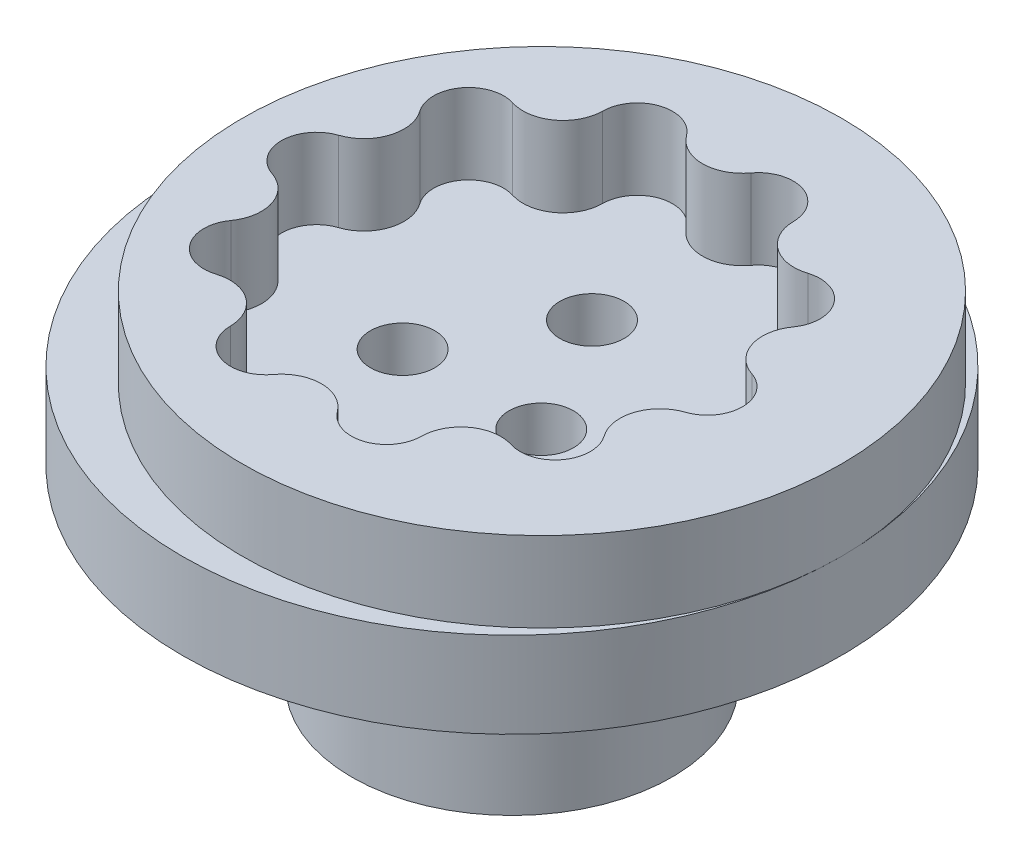
SolidWorks part; units mm, degrees
material "6061 Alloy"
ref_plane "Front" through (0, 0, 0) normal (0, 0, 1) x (1, 0, 0)
ref_plane "Top" through (0, 0, 0) normal (0, 1, 0) x (1, 0, 0)
ref_plane "Right" through (0, 0, 0) normal (1, 0, 0) x (0, 0, -1)
sketch "Sketch1" plane through (0, 0, 0) normal (0, 1, 0) x (1, 0, 0)
  circle A0 centre (0, 0) radius 26.1937 construction
  circle A1 centre (0, 0) radius 26.143
  dimension "D1" = 52.3875
  dimension "D2" = 0.0508
extrude "Boss-Extrude1" add sketch "Sketch1" against normal blind 6.8104
sketch "Sketch2" plane through (0, -6.8104, 0) normal (0, -1, 0) x (1, 0, 0)
  circle A0 centre (0, 0) radius 12.7
  dimension "D1" = 25.4
extrude "Boss-Extrude2" add sketch "Sketch2" along normal blind 15.0812
sketch "Sketch3" plane through (0, 0, 0) normal (0, 1, 0) x (1, 0, 0)
  line L0 (0, 0) -> (0, 26.143) construction
  line L1 (0, 0) -> (15.3664, 21.1501) construction
  arc A0 (2.553, 16.4005) -> (7.5745, 14.7689) centre (4.7912, 14.7457) cw
  circle A2 centre (0, 0) radius 18.288 construction
  arc A3 (0, 15.113) -> (2.553, 16.4005) centre (0, 18.288) ccw
  arc A4 (8.8832, 12.2267) -> (7.5745, 14.7689) centre (10.7494, 14.7953) cw
  arc A5 (8.8832, 12.2267) -> (11.7054, 11.7676) centre (10.7494, 14.7953) ccw
  arc A6 (11.7054, 11.7676) -> (14.8088, 7.4961) centre (12.5434, 9.1133) cw
  arc A7 (14.3733, 4.6702) -> (14.8088, 7.4961) centre (17.3929, 5.6513) cw
  arc A8 (14.3733, 4.6702) -> (16.3867, 2.64) centre (17.3929, 5.6513) ccw
  arc A9 (16.3867, 2.64) -> (16.3867, -2.64) centre (15.5045, 0) cw
  arc A10 (14.3733, -4.6702) -> (16.3867, -2.64) centre (17.3929, -5.6513) cw
  arc A11 (14.3733, -4.6702) -> (14.8088, -7.4961) centre (17.3929, -5.6513) ccw
  arc A12 (14.8088, -7.4961) -> (11.7054, -11.7676) centre (12.5434, -9.1133) cw
  arc A13 (8.8832, -12.2267) -> (11.7054, -11.7676) centre (10.7494, -14.7953) cw
  arc A14 (8.8832, -12.2267) -> (7.5745, -14.7689) centre (10.7494, -14.7953) ccw
  arc A15 (7.5745, -14.7689) -> (2.553, -16.4005) centre (4.7912, -14.7457) cw
  arc A16 (0, -15.113) -> (2.553, -16.4005) centre (0, -18.288) cw
  arc A17 (0, -15.113) -> (-2.553, -16.4005) centre (0, -18.288) ccw
  arc A18 (-2.553, -16.4005) -> (-7.5745, -14.7689) centre (-4.7912, -14.7457) cw
  arc A19 (-8.8832, -12.2267) -> (-7.5745, -14.7689) centre (-10.7494, -14.7953) cw
  arc A20 (-8.8832, -12.2267) -> (-11.7054, -11.7676) centre (-10.7494, -14.7953) ccw
  arc A21 (-11.7054, -11.7676) -> (-14.8088, -7.4961) centre (-12.5434, -9.1133) cw
  arc A22 (-14.3733, -4.6702) -> (-14.8088, -7.4961) centre (-17.3929, -5.6513) cw
  arc A23 (-14.3733, -4.6702) -> (-16.3867, -2.64) centre (-17.3929, -5.6513) ccw
  arc A24 (-16.3867, -2.64) -> (-16.3867, 2.64) centre (-15.5045, 0) cw
  arc A25 (-14.3733, 4.6702) -> (-16.3867, 2.64) centre (-17.3929, 5.6513) cw
  arc A26 (-14.3733, 4.6702) -> (-14.8088, 7.4961) centre (-17.3929, 5.6513) ccw
  arc A27 (-14.8088, 7.4961) -> (-11.7054, 11.7676) centre (-12.5434, 9.1133) cw
  arc A28 (-8.8832, 12.2267) -> (-11.7054, 11.7676) centre (-10.7494, 14.7953) cw
  arc A29 (-8.8832, 12.2267) -> (-7.5745, 14.7689) centre (-10.7494, 14.7953) ccw
  arc A30 (-7.5745, 14.7689) -> (-2.553, 16.4005) centre (-4.7912, 14.7457) cw
  arc A31 (0, 15.113) -> (-2.553, 16.4005) centre (0, 18.288) cw
  circle A32 centre (0, 0) radius 26.143
  circle A33 centre (0, 0) radius 26.143 construction
  point P78 (0, 0)
  dimension "D1" = 36.576
  dimension "D2" = 3.175
  dimension "D3" = 36
extrude "Boss-Extrude3" add sketch "Sketch3" along normal blind 6.35
hole_wizard "1/4-20 Tapped Hole1" positions "Sketch5" profile "Sketch4" tap size "1/4-20" standard "ANSI Inch" end condition through all
sketch "Sketch5" plane through (0, -21.8916, 0) normal (0, -1, 0) x (-1, 0, 0)
  circle A1 centre (0, 0) radius 6.35
  circle A3 centre (0, 0) radius 12.7 construction
  point P2 (0, 6.35)
  point P23 (5.4993, -3.175)
  point P24 (-5.4993, -3.175)
  dimension "D2" = 3
sketch "Sketch4" plane through (0, -21.8916, -6.35) normal (1, 0, 0) x (0, 0, -1)
  line L0 (0, 0) -> (0, 28.2416)
  line L1 (0, 28.2416) -> (2.5527, 28.2416)
  line L2 (2.5527, 28.2416) -> (2.5527, 0)
  line L5 (2.5527, 0) -> (0, 0)
  line L11 (0, -6.35) -> (0, 107.95) construction
  dimension "Thread Major Dia." = 5.1054
  dimension "Thru Tap Drill Depth" = 28.2416
sketch "Sketch6" plane through (0, 6.35, 0) normal (0, 1, 0) x (1, 0, 0)
  line L0 (-26.143, 0) -> (26.143, 0) construction
  line L2 (-33.2518, 33.8083) -> (33.2518, 33.8083)
  line L3 (-33.2518, 33.8083) -> (-33.2518, -33.8083)
  line L4 (-33.2518, -33.8083) -> (33.2518, -33.8083)
  line L5 (33.2518, 33.8083) -> (33.2518, -33.8083)
  line L6 (-33.2518, 33.8083) -> (33.2518, -33.8083) construction
  line L7 (-33.2518, -33.8083) -> (33.2518, 33.8083) construction
  circle A0 centre (0, 0) radius 26.143 construction
  arc A1 (26.143, 0) -> (-21.3805, 0) centre (2.3812, 0) cw
  arc A2 (26.143, 0) -> (-21.3805, 0) centre (2.3812, 0) ccw
  point P7 (0, 0)
  dimension "D1" = 4.7625
extrude "Cut-Extrude2" cut sketch "Sketch6" against normal blind 6.35
